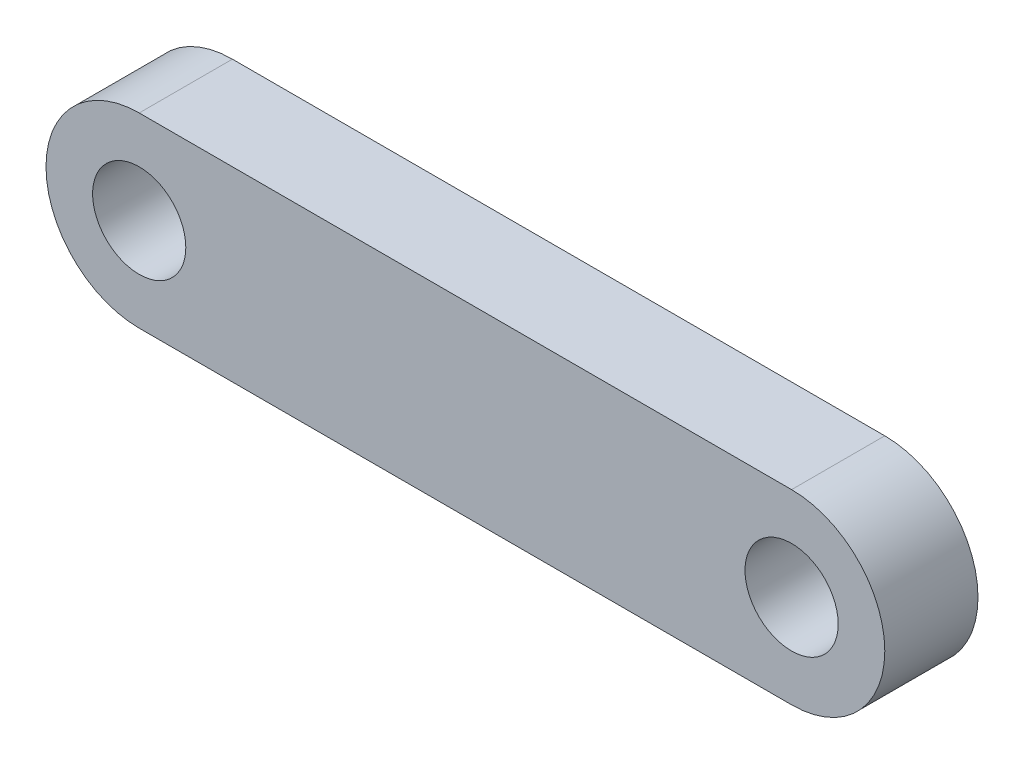
SolidWorks part; units mm, degrees
material "1023 碳钢板 (SS)"
ref_plane "前视基准面" through (0, 0, 0) normal (0, 0, 1) x (1, 0, 0)
ref_plane "上视基准面" through (0, 0, 0) normal (0, 1, 0) x (1, 0, 0)
ref_plane "右视基准面" through (0, 0, 0) normal (1, 0, 0) x (0, 0, -1)
sketch "草图1" plane through (0, 0, 0) normal (0, 0, 1) x (1, 0, 0)
  line L0 (0, 50) -> (350, 50)
  line L1 (0, -50) -> (350, -50)
  arc A0 (0, 50) -> (0, -50) centre (0, 0) ccw
  circle A1 centre (0, 0) radius 25
  arc A2 (350, -50) -> (350, 50) centre (350, 0) ccw
  circle A3 centre (350, 0) radius 25
  dimension "D1" = 50
  dimension "D2" = 50
  dimension "D5" = 350
extrude "拉伸1" add sketch "草图1" along normal blind 50
